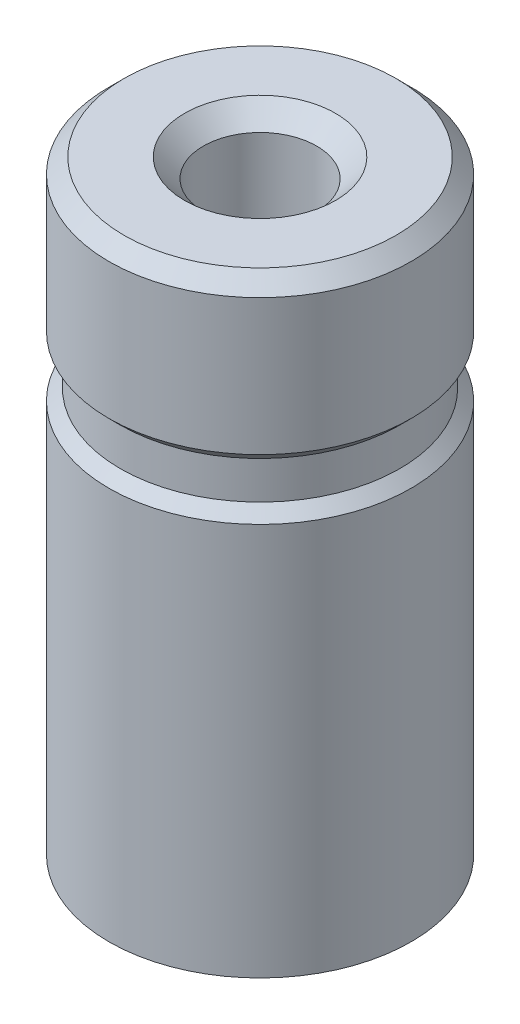
SolidWorks part; units mm, degrees
material "Custom Metal"
ref_plane "Front Plane" through (0, 0, 0) normal (0, 0, 1) x (1, 0, 0)
ref_plane "Top Plane" through (0, 0, 0) normal (0, 1, 0) x (1, 0, 0)
ref_plane "Right Plane" through (0, 0, 0) normal (1, 0, 0) x (0, 0, -1)
sketch "Sketch1" plane through (0, 0, 0) normal (0, 1, 0) x (1, 0, 0)
  circle A0 centre (0, 0) radius 2
  dimension "D1" = 4
extrude "Boss-Extrude1" add sketch "Sketch1" along normal blind 5.2
sketch "Sketch3" plane through (0, 5.2, 0) normal (0, 1, 0) x (1, 0, 0)
  circle A0 centre (0, 0) radius 2
  circle A1 centre (0, 0) radius 2 construction
extrude "Boss-Extrude2" add sketch "Sketch3" along normal blind 0.15 draft 45
sketch "Sketch4" plane through (0, 5.35, 0) normal (0, 1, 0) x (1, 0, 0)
  circle A0 centre (0, 0) radius 1.85
  circle A1 centre (0, 0) radius 1.85 construction
extrude "Boss-Extrude3" add sketch "Sketch4" along normal blind 0.5
sketch "Sketch5" plane through (0, 5.85, 0) normal (0, 1, 0) x (1, 0, 0)
  circle A0 centre (0, 0) radius 1.85
  circle A1 centre (0, 0) radius 1.85 construction
extrude "Boss-Extrude4" add sketch "Sketch5" along normal blind 0.15 draft 45 draft outward yes
sketch "Sketch6" plane through (0, 6, 0) normal (0, 1, 0) x (1, 0, 0)
  circle A0 centre (0, 0) radius 2
  circle A1 centre (0, 0) radius 2 construction
extrude "Boss-Extrude5" add sketch "Sketch6" along normal blind 1.8
sketch "Sketch7" plane through (0, 7.8, 0) normal (0, 1, 0) x (1, 0, 0)
  circle A0 centre (0, 0) radius 2
  circle A1 centre (0, 0) radius 2 construction
extrude "Boss-Extrude6" add sketch "Sketch7" along normal blind 0.2 draft 45
sketch "Sketch11" plane through (0, 8, 0) normal (0, 1, 0) x (1, 0, 0)
  circle A0 centre (0, 0) radius 1
  dimension "D1" = 2
extrude "Cut-Extrude1" cut sketch "Sketch11" against normal blind 0.25 draft 45
sketch "Sketch12" plane through (0, 7.75, 0) normal (0, 1, 0) x (1, 0, 0)
  circle A0 centre (0, 0) radius 0.75
  circle A1 centre (0, 0) radius 0.75 construction
extrude "Cut-Extrude2" cut sketch "Sketch12" against normal blind 4
